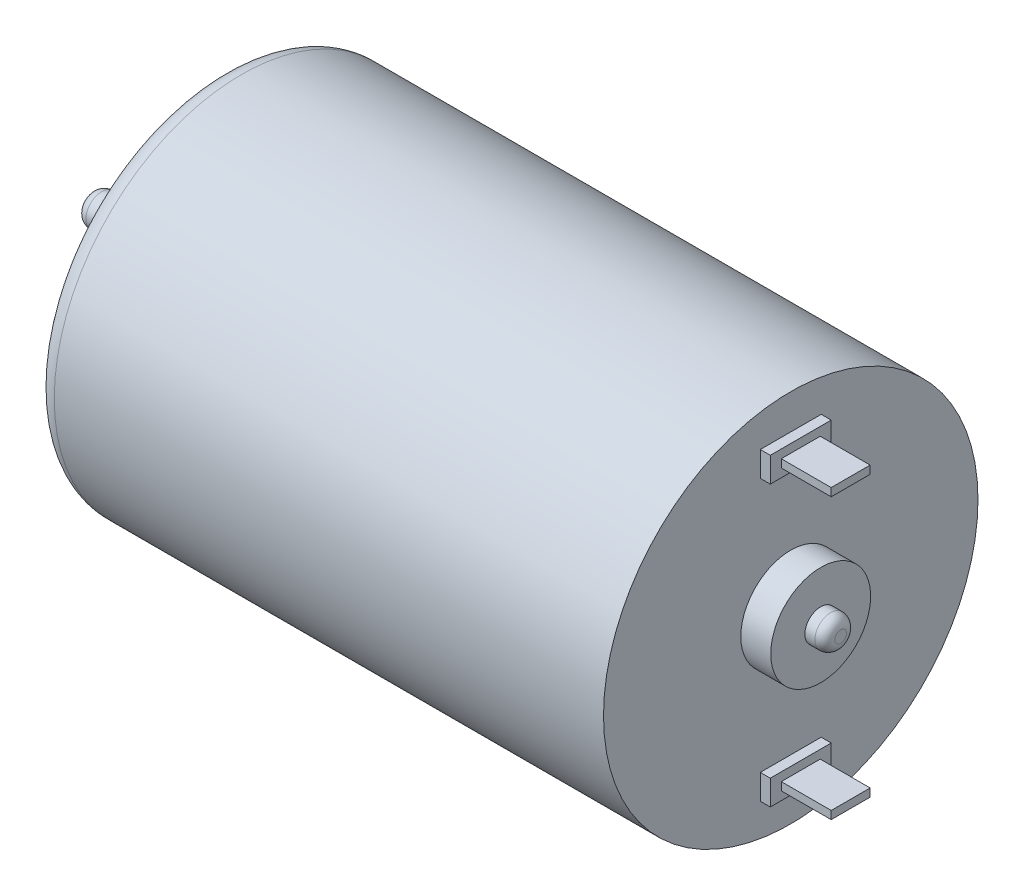
SolidWorks part; units mm, degrees
ref_plane "Ebene vorne" through (0, 0, 0) normal (0, 0, 1) x (1, 0, 0)
ref_plane "Ebene oben" through (0, 0, 0) normal (0, 1, 0) x (1, 0, 0)
ref_plane "Ebene rechts" through (0, 0, 0) normal (1, 0, 0) x (0, 0, -1)
sketch "MainLayout" plane through (0, 0, 0) normal (0, 0, 1) x (1, 0, 0)
  line L0 (0, 0) -> (66.5, 0) construction
  line L1 (0, 0) -> (-8.5, 0) construction
  line L2 (-8.5, 0) -> (-8.5, 1.5875) construction
  line L3 (-8.5, 1.5875) -> (0, 1.5875) construction
  line L4 (0, 0) -> (0, 6.5) construction
  line L5 (0, 6.5) -> (4.5, 6.5) construction
  line L6 (4.5, 6.5) -> (4.5, 18.75) construction
  line L7 (4.5, 18.75) -> (61.5, 18.75) construction
  line L8 (61.5, 18.75) -> (61.5, 5) construction
  line L9 (61.5, 5) -> (64.5, 5) construction
  line L10 (64.5, 5) -> (64.5, 1.5875) construction
  line L11 (64.5, 1.5875) -> (66.5, 1.5875) construction
  line L12 (66.5, 1.5875) -> (66.5, 0) construction
  line L13 (64.5, 1.5875) -> (64.5, 0) construction
  line L14 (64.5, 1.5875) -> (0, 1.5875) construction
  line L15 (61.5, 14) -> (62.5, 14) construction
  line L16 (62.5, 14) -> (67.5, 14) construction
  point P3 (61.5, 14)
  point P15 (4.5, 12.5)
  point P19 (68.4309, 14)
  dimension "D1" = 13
  dimension "D2" = 4.5
  dimension "D3" = 57
  dimension "D4" = 75
  dimension "D5" = 3
  dimension "D6" = 3.175
  dimension "D7" = 13
  dimension "D8" = 37.5
  dimension "D9" = 10
  dimension "D10" = 25
  dimension "D11" = 28
  dimension "D12" = 1
  dimension "D13" = 5
sketch "Anschluss" plane through (0, 0, 0) normal (1, 0, 0) x (0, 0, -1)
  line L0 (0, 15.25) -> (0, 12.75) construction
  line L1 (3.05, 15.25) -> (-3.05, 15.25) construction
  line L2 (3.05, 15.25) -> (3.05, 12.75) construction
  line L3 (3.05, 12.75) -> (-3.05, 12.75) construction
  line L4 (-3.05, 15.25) -> (-3.05, 12.75) construction
  line L5 (-3.05, 14) -> (3.05, 14) construction
  line L7 (1.95, 14.4) -> (-1.95, 14.4) construction
  line L8 (1.95, 14.4) -> (1.95, 13.6) construction
  line L9 (1.95, 13.6) -> (-1.95, 13.6) construction
  line L10 (-1.95, 14.4) -> (-1.95, 13.6) construction
  point P10 (0, 14)
  point P16 (-1.95, 14)
  point P17 (0, 14.4)
  point P18 (-1.3148, 14.4358)
  dimension "D1" = 6.1
  dimension "D2" = 3.9
  dimension "D3" = 0.8
  dimension "D4" = 2.5
sketch "Skizze3" plane through (0, 0, 0) normal (0, 0, 1) x (1, 0, 0)
  line L0 (66.5, 1.5875) -> (66.5, 0) construction
  line L1 (64.5, 1.5875) -> (66.5, 1.5875) construction
  line L2 (64.5, 1.5875) -> (0, 1.5875) construction
  line L3 (0, 0) -> (66.5, 0) construction
  line L4 (0, 0) -> (-8.5, 0) construction
  line L5 (-8.5, 0) -> (-8.5, 1.5875) construction
  line L6 (-8.5, 1.5875) -> (0, 1.5875) construction
  line L7 (66.5, 1.5875) -> (66.5, 0)
  line L8 (64.5, 1.5875) -> (66.5, 1.5875)
  line L9 (64.5, 1.5875) -> (0, 1.5875)
  line L10 (0, 0) -> (66.5, 0)
  line L11 (0, 0) -> (-8.5, 0)
  line L12 (-8.5, 0) -> (-8.5, 1.5875)
  line L13 (-8.5, 1.5875) -> (0, 1.5875)
revolve "Rotation1" add sketch "Skizze3" angle 360 about L0
fillet "Verrundung1" radius 1 2 edges at (-8.5, 0, 1.5875) (66.5, 0, 1.5875)
sketch "Skizze4" plane through (0, 0, 0) normal (0, 0, 1) x (1, 0, 0)
  line L0 (64.5, 1.5875) -> (0, 1.5875) construction
  line L1 (64.5, 5) -> (64.5, 1.5875) construction
  line L2 (61.5, 5) -> (64.5, 5) construction
  line L3 (61.5, 18.75) -> (61.5, 5) construction
  line L4 (4.5, 18.75) -> (61.5, 18.75) construction
  line L5 (4.5, 6.5) -> (4.5, 18.75) construction
  line L6 (0, 6.5) -> (4.5, 6.5) construction
  line L7 (0, 0) -> (0, 6.5) construction
  line L8 (64.5, 1.5875) -> (0, 1.5875)
  line L9 (64.5, 5) -> (64.5, 1.5875)
  line L10 (61.5, 5) -> (64.5, 5)
  line L11 (61.5, 18.75) -> (61.5, 5)
  line L12 (4.5, 18.75) -> (61.5, 18.75)
  line L13 (4.5, 6.5) -> (4.5, 18.75)
  line L14 (0, 6.5) -> (4.5, 6.5)
  line L15 (0, 1.5875) -> (0, 6.5)
revolve "Rotation2" add sketch "Skizze4" angle 360 about L0
hole_wizard "M3 Gewindebohrung1" positions "Skizze7" profile "Skizze8" tap size "M3" standard "DIN"
sketch "Skizze7" plane through (4.5, 0, 0) normal (-1, 0, 0) x (0, 0, 1)
  point P0 (0, 12.5)
sketch "Skizze8" plane through (4.5, 12.5, 0) normal (0, 1, 0) x (0, 0, 1)
  line L0 (0, 0) -> (0, 9.2511)
  line L1 (0, 9.2511) -> (1.25, 8.5)
  line L2 (1.25, 8.5) -> (1.25, 0)
  line L5 (1.25, 0) -> (0, 0)
  line L10 (0, 9.2511) -> (-1.25, 8.5) construction
  line L11 (0, -6.35) -> (0, 107.95) construction
  dimension "Bohrerdurchmesser" = 2.5
  dimension "Bohrungstiefe" = 8.5
  dimension "Spitzenwinkel" = 118
cosmetic thread "Bohrungsgewinde1" parameters "D1"=6, "D2"=3
fillet "Verrundung2" radius 2 1 edges at (4.5, 0, 18.75)
chamfer "Fase1" distance 0.5 angle 45 1 edges at (0, 0, 6.5)
sketch "Skizze5" plane through (61.5, 0, 0) normal (1, 0, 0) x (0, 0, -1)
  line L0 (3.05, 15.25) -> (3.05, 12.75) construction
  line L1 (3.05, 12.75) -> (-3.05, 12.75) construction
  line L2 (-3.05, 15.25) -> (-3.05, 12.75) construction
  line L3 (3.05, 15.25) -> (-3.05, 15.25) construction
  line L4 (3.05, 15.25) -> (3.05, 12.75)
  line L5 (3.05, 12.75) -> (-3.05, 12.75)
  line L6 (-3.05, 15.25) -> (-3.05, 12.75)
  line L7 (3.05, 15.25) -> (-3.05, 15.25)
extrude "Aufsatz-Linear austragen1" add sketch "Skizze5" along normal up to vertex (1 mm away) separate body up to point (62.5, 14, 0)
sketch "Skizze6" plane through (62.5, 0, 0) normal (1, 0, 0) x (0, 0, -1)
  line L0 (1.95, 14.4) -> (1.95, 13.6) construction
  line L1 (-1.95, 14.4) -> (-1.95, 13.6) construction
  line L2 (1.95, 13.6) -> (-1.95, 13.6) construction
  line L3 (1.95, 14.4) -> (-1.95, 14.4) construction
  line L4 (1.95, 14.4) -> (1.95, 13.6)
  line L5 (-1.95, 14.4) -> (-1.95, 13.6)
  line L6 (1.95, 13.6) -> (-1.95, 13.6)
  line L7 (1.95, 14.4) -> (-1.95, 14.4)
extrude "Aufsatz-Linear austragen2" add sketch "Skizze6" along normal up to vertex (5 mm away) separate body up to point (67.5, 14, 0)
mirror "Spiegeln1" about plane through (0, 0, 0) normal (0, 1, 0) of "M3 Gewindebohrung1"
cosmetic thread "Bohrungsgewinde2" parameters "D1"=6, "D2"=3
mirror "Spiegeln5" about plane through (0, 0, 0) normal (0, 1, 0) of bodies 103 104
